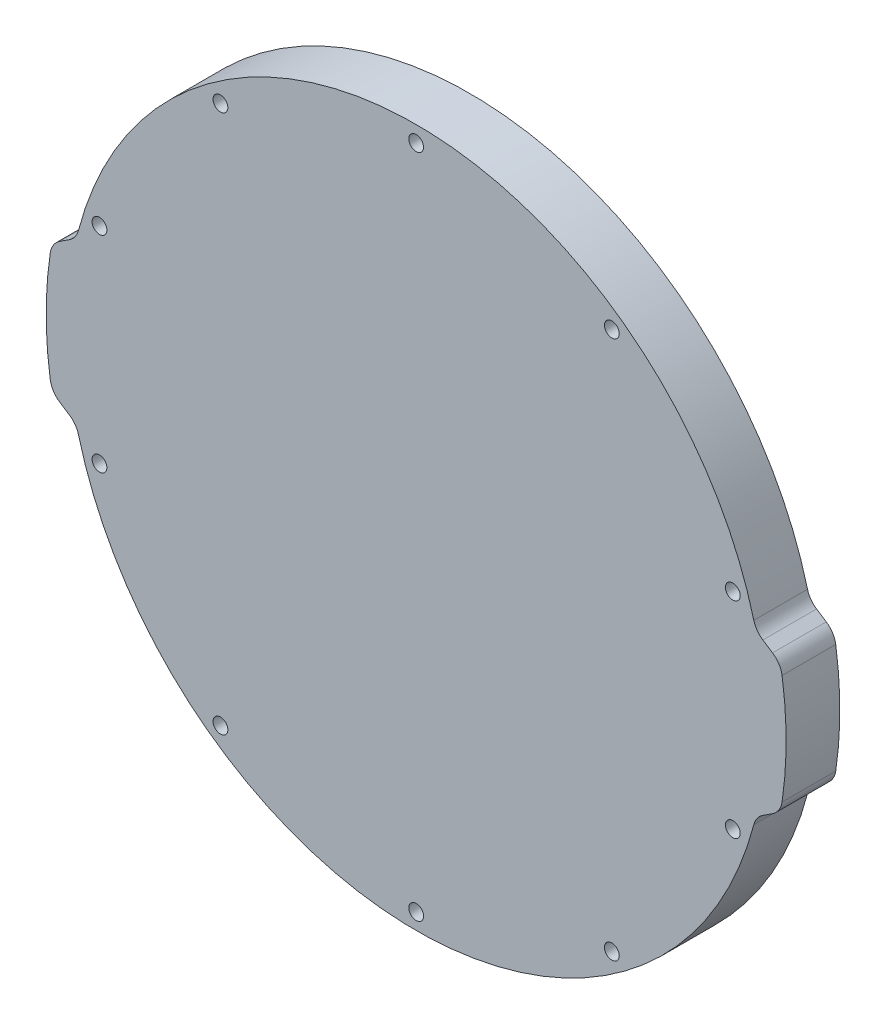
SolidWorks part; units mm, degrees
material "Acrylic (Medium-high impact)"
ref_plane "Front Plane" through (0, 0, 0) normal (0, 0, 1) x (1, 0, 0)
ref_plane "Top Plane" through (0, 0, 0) normal (0, 1, 0) x (1, 0, 0)
ref_plane "Right Plane" through (0, 0, 0) normal (1, 0, 0) x (0, 0, -1)
sketch "Sketch1" plane through (0, 0, 0) normal (0, 0, 1) x (1, 0, 0)
  line L0 (-87.5, 0) -> (87.5, 0) construction
  line L1 (0, -87.5) -> (0, 87.5) construction
  line L2 (-86.1626, 15.24) -> (-80.3219, 19.05)
  line L3 (86.1626, 15.24) -> (80.3219, 19.05)
  line L4 (-86.1626, -15.24) -> (-80.3219, -19.05)
  line L5 (86.1626, -15.24) -> (80.3219, -19.05)
  line L6 (0, 0) -> (24.6341, 33.9059) construction
  line L7 (0, 0) -> (-24.6341, 33.9059) construction
  arc A0 (-86.1626, 15.24) -> (-86.1626, -15.24) centre (0, 0) ccw
  arc A1 (-80.3219, 19.05) -> (-80.3219, -19.05) centre (0, 0) ccw construction
  circle A2 centre (0, 0) radius 78.74 construction
  circle A5 centre (0, 78.74) radius 1.75
  circle A10 centre (46.2822, 63.702) radius 1.75
  circle A11 centre (74.8862, 24.332) radius 1.75
  circle A12 centre (74.8862, -24.332) radius 1.75
  circle A13 centre (46.2822, -63.702) radius 1.75
  circle A14 centre (0, -78.74) radius 1.75
  circle A15 centre (-46.2822, -63.702) radius 1.75
  circle A16 centre (-74.8862, -24.332) radius 1.75
  circle A17 centre (-74.8862, 24.332) radius 1.75
  circle A18 centre (-46.2822, 63.702) radius 1.75
  arc A19 (86.1626, 15.24) -> (-86.1626, 15.24) centre (0, 0) ccw construction
  arc A20 (86.1626, -15.24) -> (86.1626, 15.24) centre (0, 0) ccw
  arc A21 (-86.1626, -15.24) -> (86.1626, -15.24) centre (0, 0) ccw construction
  arc A22 (80.3219, 19.05) -> (-80.3219, 19.05) centre (0, 0) ccw
  arc A23 (80.3219, -19.05) -> (80.3219, 19.05) centre (0, 0) ccw construction
  arc A24 (-80.3219, -19.05) -> (80.3219, -19.05) centre (0, 0) ccw
  circle A25 centre (0, 0) radius 63.5 construction
  circle A26 centre (0, 0) radius 41.91 construction
  circle A27 centre (24.6341, 33.9059) radius 5.08
  circle A28 centre (-24.6341, 33.9059) radius 5.08
  dimension "D2" = 157.48
  dimension "D3" = 165.1
  dimension "D4" = 175
  dimension "D5" = 3.5
  dimension "D6" = 127
  dimension "D7" = 10.16
  dimension "D12" = 83.82
  dimension "D9" = 19.05
  dimension "D10" = 15.24
  dimension "D11" = 72
  dimension "D8" = 10
extrude "Boss-Extrude1" add sketch "Sketch1" along normal mid plane 12.7 contours A28 | L4 A24 L5 A20 L3 A22 L2 A0 A18 A17 A16 A15 A14 A13 A12 A11 A10 A5 A27 A28
fillet "Fillet1" radius 5.08 8 edges at (-86.1626, 15.24, 0) (-80.3219, 19.05, 0) (-86.1626, -15.24, 0) (-80.3219, -19.05, 0) (86.1626, -15.24, 0) (80.3219, -19.05, 0) (86.1626, 15.24, 0) (80.3219, 19.05, 0)
